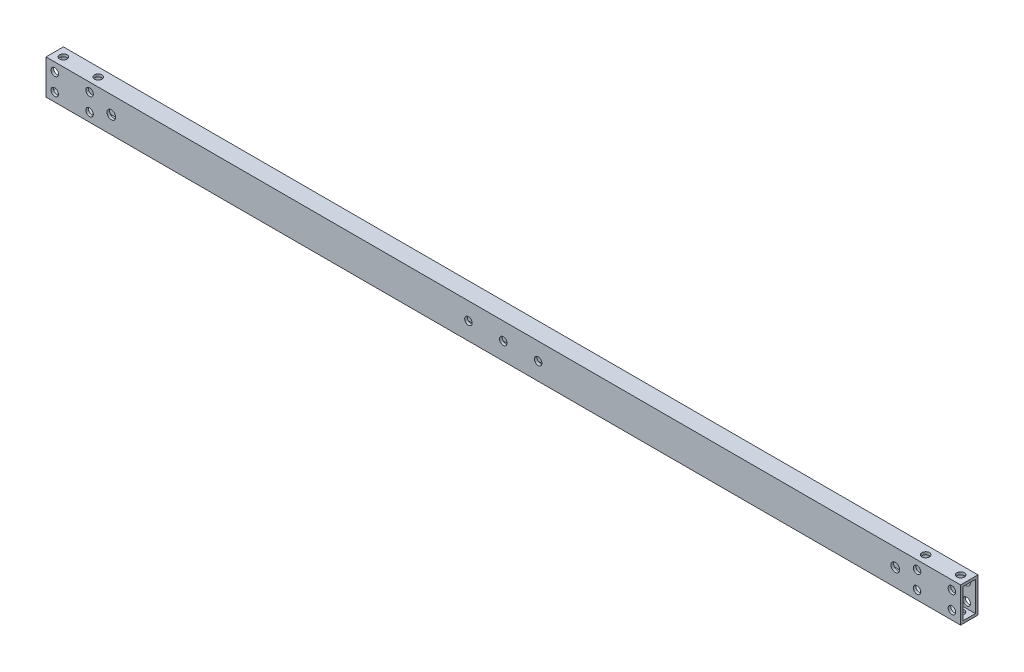
SolidWorks part; units mm, degrees
material "5052-H34"
ref_plane "正面" through (0, 0, 0) normal (0, 0, 1) x (1, 0, 0)
ref_plane "平面" through (0, 0, 0) normal (0, 1, 0) x (1, 0, 0)
ref_plane "右側面" through (0, 0, 0) normal (1, 0, 0) x (0, 0, -1)
sketch "ｽｹｯﾁ1" plane through (0, 0, 0) normal (1, 0, 0) x (0, 0, -1)
  line L1 (-5, 10) -> (5, 10)
  line L2 (-5, 10) -> (-5, -10)
  line L3 (-5, -10) -> (5, -10)
  line L4 (5, 10) -> (5, -10)
  line L5 (-5, 10) -> (5, -10) construction
  line L6 (-5, -10) -> (5, 10) construction
  point P0 (0, 0)
  dimension "D1" = 10
  dimension "D2" = 20
extrude "押し出し-薄板1" add sketch "ｽｹｯﾁ1" along normal blind 525 thin
sketch "ｽｹｯﾁ2" plane through (0, 0, 5) normal (0, 0, 1) x (1, 0, 0)
  line L0 (262.5, 10) -> (262.5, -10) construction
  line L1 (525, 10) -> (0, 10) construction
  line L2 (525, -10) -> (0, -10) construction
  line L4 (525, 10) -> (525, -10) construction
  line L5 (262.5, 0) -> (282.5, 0) construction
  line L6 (0, 0) -> (525, 0) construction
  circle A5 centre (282.5, 0) radius 2.15
  circle A6 centre (262.5, 0) radius 2.15
  circle A7 centre (242.5, 0) radius 2.15
  circle A8 centre (487.5, 0) radius 2.5
  circle A9 centre (37.5, 0) radius 2.5
  circle A10 centre (520, 5) radius 2.15
  circle A11 centre (520, -5) radius 2.15
  circle A12 centre (500, 5) radius 2.15
  circle A13 centre (500, -5) radius 2.15
  circle A14 centre (25, -5) radius 2.15
  circle A15 centre (25, 5) radius 2.15
  circle A16 centre (5, -5) radius 2.15
  circle A17 centre (5, 5) radius 2.15
  dimension "D1" = 4.3
  dimension "D2" = 4.3
  dimension "D5" = 450
  dimension "D6" = 5
  dimension "D3" = 5
  dimension "D7" = 5
  dimension "D8" = 20
  dimension "D4" = 20
extrude "ｶｯﾄ - 押し出し1" cut sketch "ｽｹｯﾁ2" against normal through all
sketch "ｽｹｯﾁ3" plane through (0, 10, 0) normal (0, 1, 0) x (1, 0, 0)
  line L0 (0, 0) -> (525, 0) construction
  line L1 (0, 5) -> (0, -5) construction
  line L2 (525, 5) -> (525, -5) construction
  line L3 (262.5, 5) -> (262.5, -5) construction
  line L4 (525, 5) -> (0, 5) construction
  line L5 (525, -5) -> (0, -5) construction
  circle A0 centre (5, 0) radius 2.15
  circle A1 centre (25, 0) radius 2.15
  circle A2 centre (500, 0) radius 2.15
  circle A3 centre (520, 0) radius 2.15
  dimension "D1" = 4.3
  dimension "D2" = 5
  dimension "D3" = 20
extrude "ｶｯﾄ - 押し出し2" cut sketch "ｽｹｯﾁ3" against normal up to surface (20 mm away) up to face at (262.5, -10, 0)
